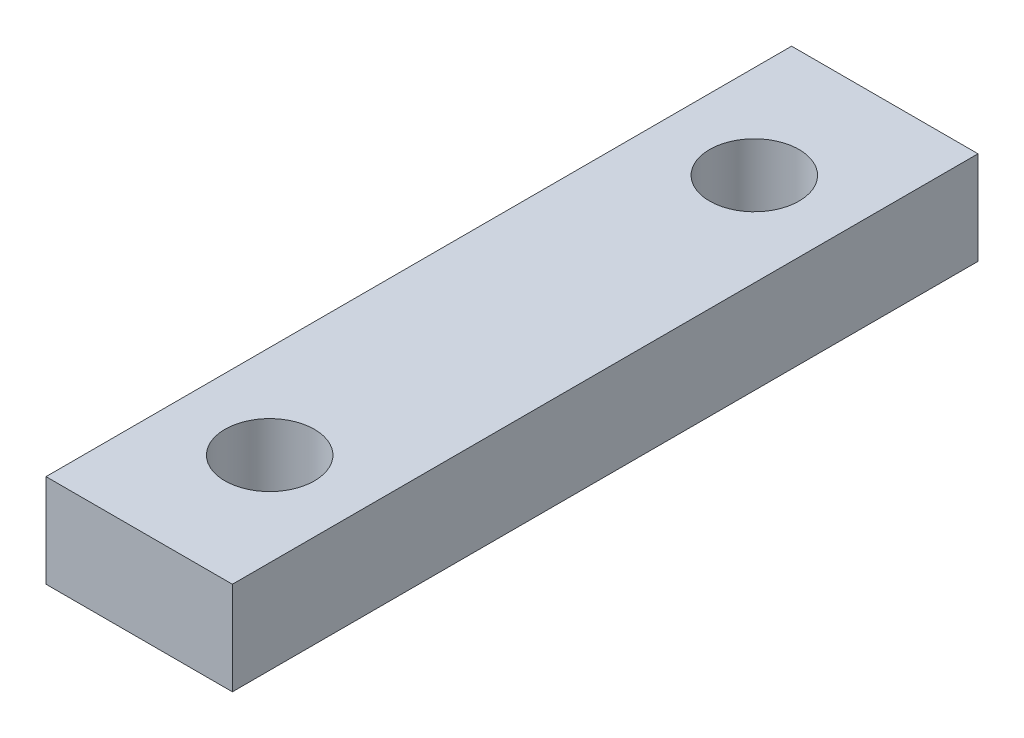
SolidWorks part; units mm, degrees
ref_plane "Front Plane" through (0, 0, 0) normal (0, 0, 1) x (1, 0, 0)
ref_plane "Top Plane" through (0, 0, 0) normal (0, 1, 0) x (1, 0, 0)
ref_plane "Right Plane" through (0, 0, 0) normal (1, 0, 0) x (0, 0, -1)
sketch "Sketch1" plane through (0, 0, 0) normal (0, 1, 0) x (1, 0, 0)
  line L0 (0, 36.6327) -> (0, -30.7143) construction
  line L1 (-42.9915, 0.0475) -> (37.6208, 0.0475) construction
  line L2 (-5, 20.0475) -> (5, 20.0475)
  line L3 (5, 20.0475) -> (5, -19.9525)
  line L4 (5, -19.9525) -> (-5, -19.9525)
  line L5 (-5, 20.0475) -> (-5, -19.9525)
  circle A0 centre (0, 13.0475) radius 2.4
  circle A1 centre (0, -12.9525) radius 2.4
  point P10 (0, -19.9525)
  point P11 (0, 20.0475)
  dimension "D3" = 4.8
  dimension "D1" = 40
  dimension "D2" = 10
  dimension "D4" = 26
extrude "Boss-Extrude1" add sketch "Sketch1" along normal blind 5
